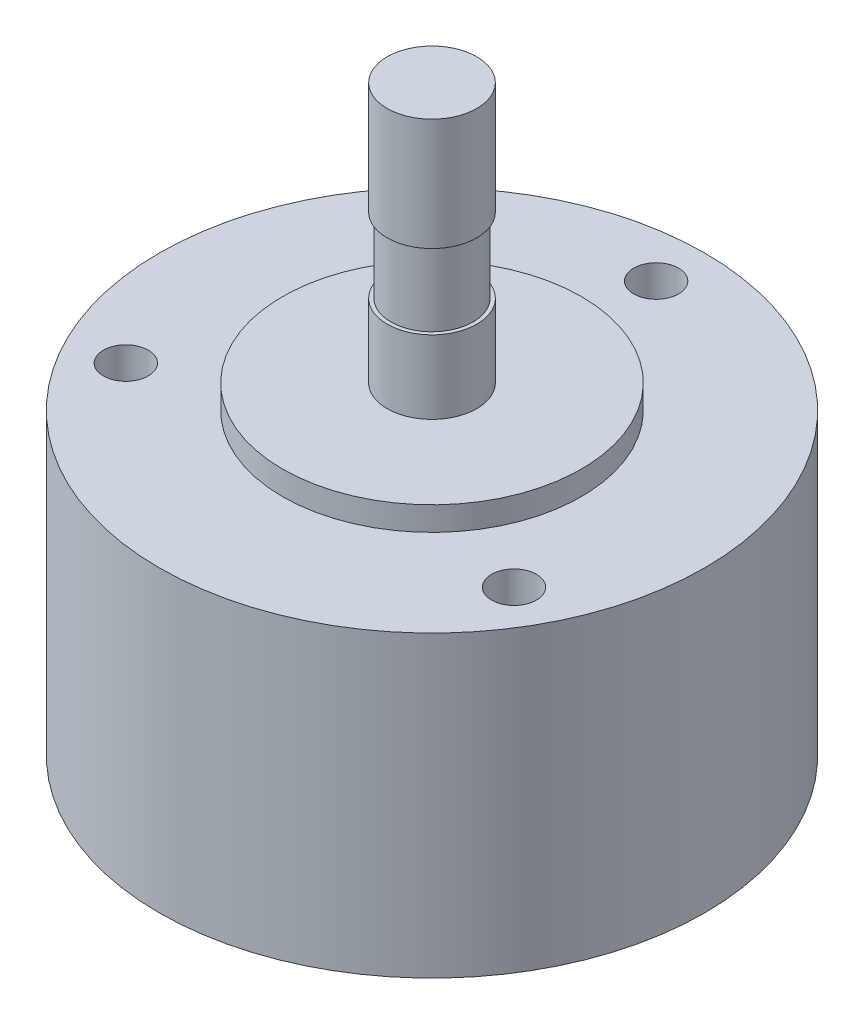
SolidWorks part; units mm, degrees
ref_plane "Front Plane" through (0, 0, 0) normal (0, 0, 1) x (1, 0, 0)
ref_plane "Top Plane" through (0, 0, 0) normal (0, 1, 0) x (1, 0, 0)
ref_plane "Right Plane" through (0, 0, 0) normal (1, 0, 0) x (0, 0, -1)
sketch "Sketch1" plane through (0, 0, 0) normal (0, 1, 0) x (1, 0, 0)
  circle A0 centre (0, 0) radius 18.25
  dimension "D1" = 36.5
extrude "Boss-Extrude1" add sketch "Sketch1" along normal blind 20
sketch "Sketch2" plane through (0, 20, 0) normal (0, 1, 0) x (1, 0, 0)
  circle A0 centre (0, 0) radius 10
  dimension "D1" = 20
extrude "Boss-Extrude2" add sketch "Sketch2" along normal blind 1.6
sketch "Sketch3" plane through (0, 21.6, 0) normal (0, 1, 0) x (1, 0, 0)
  circle A0 centre (0, 0) radius 3
  dimension "D1" = 6
extrude "Boss-Extrude3" add sketch "Sketch3" along normal blind 17.4
sketch "Sketch4" plane through (0, 0, 0) normal (1, 0, 0) x (0, 0, -1)
  line L0 (3, 21.6) -> (3, 39) construction
  line L1 (3, 31.5) -> (2.75, 31.5)
  line L2 (3, 31.5) -> (3, 26.5)
  line L3 (3, 26.5) -> (2.75, 26.5)
  line L4 (2.75, 31.5) -> (2.75, 26.5)
  line L5 (18.25, 20) -> (-18.25, 20) construction
  dimension "D1" = 0.25
  dimension "D2" = 5
  dimension "D3" = 6.5
revolve "Cut-Revolve1" cut sketch "Sketch4" angle 360 about axis through (0, 39, 0) along (0, -1, 0)
sketch "Sketch5" plane through (0, 20, 0) normal (0, 1, 0) x (1, 0, 0)
  circle A0 centre (0, 0) radius 15 construction
  dimension "D1" = 30
hole_wizard "Ø3.0mm Dowel Hole1" positions "Sketch6" profile "Sketch7" hole size "Ø3.0" standard "ANSI Metric"
sketch "Sketch6" plane through (0, 20, 0) normal (0, 1, 0) x (1, 0, 0)
  circle A0 centre (0, 0) radius 15 construction
  point P0 (0, 15)
sketch "Sketch7" plane through (0, 20, -15) normal (1, 0, 0) x (0, 0, 1)
  line L0 (0, 0) -> (0, 6.9013)
  line L1 (0, 6.9013) -> (1.5, 6)
  line L2 (1.5, 6) -> (1.5, 0)
  line L5 (1.5, 0) -> (0, 0)
  line L10 (0, 6.9013) -> (-1.5, 6) construction
  line L11 (0, -6.35) -> (0, 107.95) construction
  dimension "Hole Dia." = 3
  dimension "Hole Depth" = 6
  dimension "Drill Angle" = 118
pattern_circular "CirPattern1" count 3 over 360 about axis through (0, 0, 0) along (0, 1, 0) of "Ø3.0mm Dowel Hole1"
